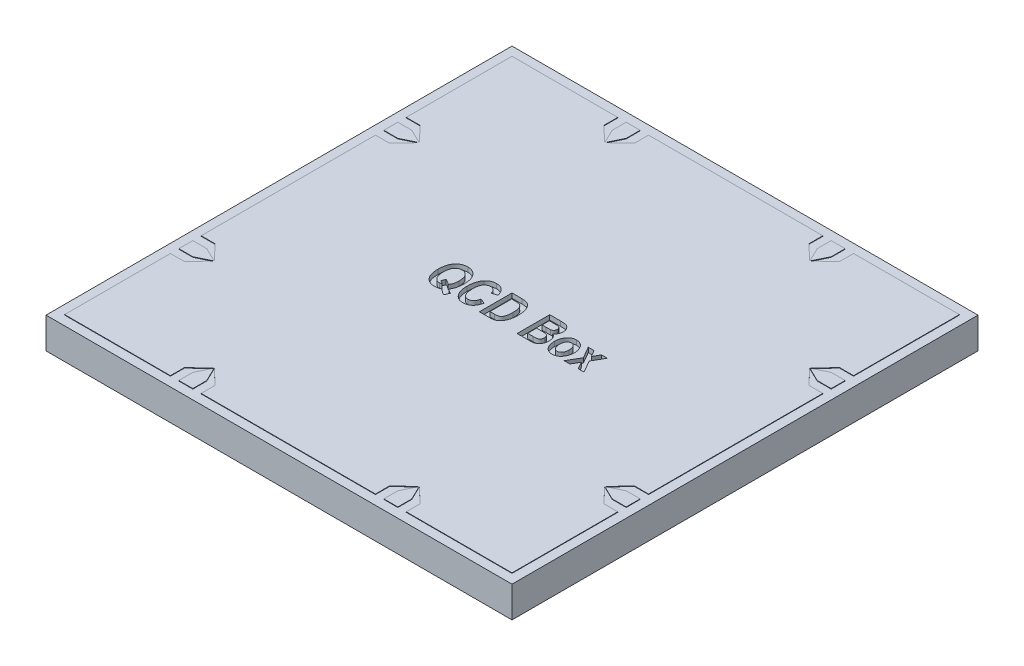
SolidWorks part; units mm, degrees
ref_plane "Front Plane" through (0, 0, 0) normal (0, 0, 1) x (1, 0, 0)
ref_plane "Top Plane" through (0, 0, 0) normal (0, 1, 0) x (1, 0, 0)
ref_plane "Right Plane" through (0, 0, 0) normal (1, 0, 0) x (0, 0, -1)
sketch "Sketch1" plane through (0, 0, 0) normal (0, 1, 0) x (1, 0, 0)
  line L1 (-5, 5) -> (5, 5)
  line L2 (-5, 5) -> (-5, -5)
  line L3 (-5, -5) -> (5, -5)
  line L4 (5, 5) -> (5, -5)
  line L5 (-5, 5) -> (5, -5) construction
  line L6 (-5, -5) -> (5, 5) construction
  point P0 (0, 0)
  dimension "D1" = 10
extrude "Boss-Extrude1" add sketch "Sketch1" along normal blind 0.675
sketch "Sketch2" plane through (0, 0.675, 0) normal (0, 1, 0) x (1, 0, 0)
  line L1 (4.8, -4.8) -> (-4.8, -4.8)
  line L2 (4.8, -4.8) -> (4.8, 4.8)
  line L3 (4.8, 4.8) -> (-4.8, 4.8)
  line L4 (-4.8, -4.8) -> (-4.8, 4.8)
  line L5 (4.8, -4.8) -> (-4.8, 4.8) construction
  line L6 (4.8, 4.8) -> (-4.8, -4.8) construction
  line L7 (5, -5) -> (-5, -5)
  line L8 (5, -5) -> (5, 5)
  line L9 (5, 5) -> (-5, 5)
  line L10 (-5, -5) -> (-5, 5)
  line L11 (5, -5) -> (-5, 5) construction
  line L12 (5, 5) -> (-5, -5) construction
  point P0 (0, 0)
  point P6 (0, 0)
  dimension "D1" = 9.6
extrude "Cut-Extrude1" cut sketch "Sketch2" against normal blind 0.01
sketch "Sketch3" plane through (0, 0.675, 0) normal (0, 1, 0) x (1, 0, 0)
  line L0 (4.8, 4.8) -> (-4.8, 4.8) construction
  line L1 (-2.53, 4.8) -> (-2.35, 4.8)
  line L2 (-2.53, 4.8) -> (-2.53, 4.5)
  line L4 (-1.87, 4.8) -> (-1.87, 4.5)
  line L5 (0, -1000) -> (0, 49000) construction
  line L6 (-4.8, 4.8) -> (-4.8, -4.8) construction
  line L7 (-2.05, 4.8) -> (-1.87, 4.8)
  line L9 (-2.35, 4.8) -> (-2.35, 4.5)
  line L11 (-2.05, 4.8) -> (-2.05, 4.5)
  line L13 (-2.53, 4.5) -> (-2.211, 4.2)
  line L14 (-2.211, 4.2) -> (-2.205, 4.2)
  line L15 (-2.205, 4.2) -> (-2.35, 4.5)
  line L16 (4.8, 4.8) -> (-4.8, 4.8) construction
  line L17 (-2.05, 4.5) -> (-2.195, 4.2)
  line L18 (-2.195, 4.2) -> (-2.189, 4.2)
  line L19 (-2.189, 4.2) -> (-1.87, 4.5)
  line L20 (2.05, 4.8) -> (1.87, 4.8)
  line L21 (1.87, 4.8) -> (1.87, 4.5)
  line L22 (2.05, 4.8) -> (2.05, 4.5)
  line L23 (2.189, 4.2) -> (1.87, 4.5)
  line L24 (2.05, 4.5) -> (2.195, 4.2)
  line L25 (2.195, 4.2) -> (2.189, 4.2)
  line L26 (2.211, 4.2) -> (2.205, 4.2)
  line L27 (2.205, 4.2) -> (2.35, 4.5)
  line L28 (2.53, 4.5) -> (2.211, 4.2)
  line L29 (2.35, 4.8) -> (2.35, 4.5)
  line L30 (2.53, 4.8) -> (2.53, 4.5)
  line L31 (2.53, 4.8) -> (2.35, 4.8)
  line L32 (4.8, 2.53) -> (4.8, 2.35)
  line L33 (4.8, 2.53) -> (4.5, 2.53)
  line L34 (4.8, 1.87) -> (4.5, 1.87)
  line L35 (4.8, 2.05) -> (4.8, 1.87)
  line L36 (4.8, 2.35) -> (4.5, 2.35)
  line L37 (4.8, 2.05) -> (4.5, 2.05)
  line L38 (4.5, 2.53) -> (4.2, 2.211)
  line L39 (4.2, 2.211) -> (4.2, 2.205)
  line L40 (4.2, 2.205) -> (4.5, 2.35)
  line L41 (4.5, 2.05) -> (4.2, 2.195)
  line L42 (4.2, 2.195) -> (4.2, 2.189)
  line L43 (4.2, 2.189) -> (4.5, 1.87)
  line L44 (4.8, -2.05) -> (4.8, -1.87)
  line L45 (4.8, -1.87) -> (4.5, -1.87)
  line L46 (4.8, -2.05) -> (4.5, -2.05)
  line L47 (4.2, -2.189) -> (4.5, -1.87)
  line L48 (4.5, -2.05) -> (4.2, -2.195)
  line L49 (4.2, -2.195) -> (4.2, -2.189)
  line L50 (4.2, -2.211) -> (4.2, -2.205)
  line L51 (4.2, -2.205) -> (4.5, -2.35)
  line L52 (4.5, -2.53) -> (4.2, -2.211)
  line L53 (4.8, -2.35) -> (4.5, -2.35)
  line L54 (4.8, -2.53) -> (4.5, -2.53)
  line L55 (4.8, -2.53) -> (4.8, -2.35)
  line L56 (2.53, -4.8) -> (2.35, -4.8)
  line L57 (2.53, -4.8) -> (2.53, -4.5)
  line L58 (1.87, -4.8) -> (1.87, -4.5)
  line L59 (2.05, -4.8) -> (1.87, -4.8)
  line L60 (2.35, -4.8) -> (2.35, -4.5)
  line L61 (2.05, -4.8) -> (2.05, -4.5)
  line L62 (2.53, -4.5) -> (2.211, -4.2)
  line L63 (2.211, -4.2) -> (2.205, -4.2)
  line L64 (2.205, -4.2) -> (2.35, -4.5)
  line L65 (2.05, -4.5) -> (2.195, -4.2)
  line L66 (2.195, -4.2) -> (2.189, -4.2)
  line L67 (2.189, -4.2) -> (1.87, -4.5)
  line L68 (-2.05, -4.8) -> (-1.87, -4.8)
  line L69 (-1.87, -4.8) -> (-1.87, -4.5)
  line L70 (-2.05, -4.8) -> (-2.05, -4.5)
  line L71 (-2.189, -4.2) -> (-1.87, -4.5)
  line L72 (-2.05, -4.5) -> (-2.195, -4.2)
  line L73 (-2.195, -4.2) -> (-2.189, -4.2)
  line L74 (-2.211, -4.2) -> (-2.205, -4.2)
  line L75 (-2.205, -4.2) -> (-2.35, -4.5)
  line L76 (-2.53, -4.5) -> (-2.211, -4.2)
  line L77 (-2.35, -4.8) -> (-2.35, -4.5)
  line L78 (-2.53, -4.8) -> (-2.53, -4.5)
  line L79 (-2.53, -4.8) -> (-2.35, -4.8)
  line L80 (-4.8, -2.53) -> (-4.8, -2.35)
  line L81 (-4.8, -2.53) -> (-4.5, -2.53)
  line L82 (-4.8, -1.87) -> (-4.5, -1.87)
  line L83 (-4.8, -2.05) -> (-4.8, -1.87)
  line L84 (-4.8, -2.35) -> (-4.5, -2.35)
  line L85 (-4.8, -2.05) -> (-4.5, -2.05)
  line L86 (-4.5, -2.53) -> (-4.2, -2.211)
  line L87 (-4.2, -2.211) -> (-4.2, -2.205)
  line L88 (-4.2, -2.205) -> (-4.5, -2.35)
  line L89 (-4.5, -2.05) -> (-4.2, -2.195)
  line L90 (-4.2, -2.195) -> (-4.2, -2.189)
  line L91 (-4.2, -2.189) -> (-4.5, -1.87)
  line L92 (-4.8, 2.05) -> (-4.8, 1.87)
  line L93 (-4.8, 1.87) -> (-4.5, 1.87)
  line L94 (-4.8, 2.05) -> (-4.5, 2.05)
  line L95 (-4.2, 2.189) -> (-4.5, 1.87)
  line L96 (-4.5, 2.05) -> (-4.2, 2.195)
  line L97 (-4.2, 2.195) -> (-4.2, 2.189)
  line L98 (-4.2, 2.211) -> (-4.2, 2.205)
  line L99 (-4.2, 2.205) -> (-4.5, 2.35)
  line L100 (-4.5, 2.53) -> (-4.2, 2.211)
  line L101 (-4.8, 2.35) -> (-4.5, 2.35)
  line L102 (-4.8, 2.53) -> (-4.5, 2.53)
  line L103 (-4.8, 2.53) -> (-4.8, 2.35)
  point P108 (0, 0)
  dimension "D1" = 0.3
  dimension "D2" = 2.27
  dimension "D3" = 0.66
  dimension "D4" = 0.3
  dimension "D5" = 0.18
  dimension "D6" = 0.6
  dimension "D7" = 0.006
  dimension "D8" = 0.01
  dimension "D9" = 4
extrude "Cut-Extrude2" cut sketch "Sketch3" against normal blind 0.01
sketch "Sketch5" plane through (0, 0.675, 0) normal (0, 1, 0) x (1, 0, 0)
  text T0 "<b>QCD Box</b>" font "Arial Narrow" height 0.7
extrude "Cut-Extrude3" cut sketch "Sketch5" against normal blind 0.1
